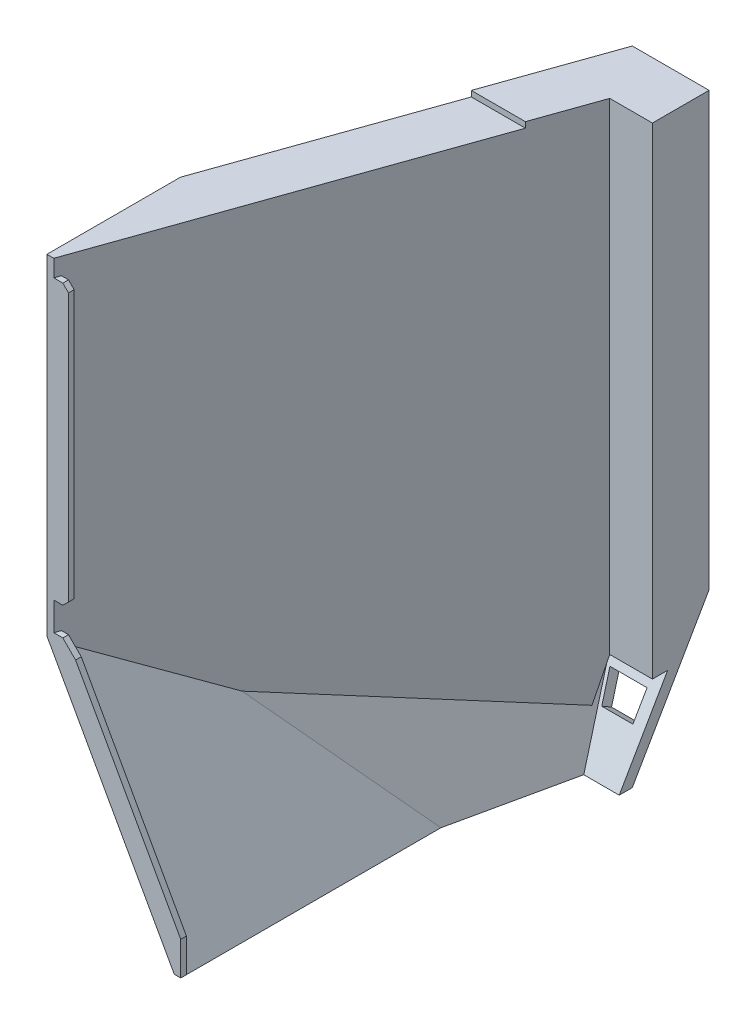
SolidWorks part; units mm, degrees
ref_plane "Plan de face" through (0, 0, 0) normal (0, 0, 1) x (1, 0, 0)
ref_plane "Plan de dessus" through (0, 0, 0) normal (0, 1, 0) x (1, 0, 0)
ref_plane "Plan de droite" through (0, 0, 0) normal (1, 0, 0) x (0, 0, -1)
sketch "Esquisse1" plane through (0, 0, 0) normal (0, 1, 0) x (1, 0, 0)
  line L0 (-258, 0) -> (-258, 609.9611) construction
  line L1 (-258, 609.9611) -> (-42.4247, 0) construction
  line L2 (-42.4247, 0) -> (-258, 0) construction
  line L3 (-42.4247, 0) -> (0, 0) construction
  line L4 (0, 0) -> (-258, 730) construction
  line L5 (-258, 609.9611) -> (-258, 730) construction
  line L6 (0, 0) -> (95.4556, 0)
  line L7 (95.4556, 0) -> (-196.1198, 825)
  line L8 (0, 0) -> (-291.5753, 825)
  line L9 (-291.5753, 825) -> (-196.1198, 825)
  line L10 (-196.1198, 825) -> (-196.1198, 0) construction
  dimension "D1" = 40
  dimension "D2" = 258
  dimension "D3" = 730
  dimension "D4" = 825
  dimension "D5" = 90
extrude "Boss.-Extru.2" add sketch "Esquisse1" along normal blind 850
sketch "Esquisse2" plane through (0, 0, -825) normal (0, 0, -1) x (-1, 0, 0)
  line L0 (196.1198, 850) -> (196.1198, 0) construction
  line L1 (196.1198, 0) -> (331.5753, 0)
  line L2 (196.1198, 0) -> (196.1198, 850)
  line L3 (196.1198, 850) -> (331.5753, 850)
  line L4 (331.5753, 0) -> (331.5753, 850)
  line L5 (196.1198, 0) -> (291.5753, 0) construction
  line L6 (196.1198, 850) -> (291.5753, 850) construction
  line L7 (291.5753, 850) -> (291.5753, 0) construction
  dimension "D1" = 40
extrude "Boss.-Extru.4" add sketch "Esquisse2" against normal blind 100
sketch "Esquisse7" plane through (-331.5753, 0, 0) normal (-1, 0, 0) x (0, 0, 1)
  line L0 (0, 850) -> (0, 0) construction
  line L1 (-615, 850) -> (0, 850)
  line L2 (-615, 850) -> (-615, 840)
  line L3 (-615, 840) -> (0, 840)
  line L4 (0, 850) -> (0, 840)
  line L5 (-725, 850) -> (0, 850) construction
  line L6 (-725, 0) -> (-725, 850) construction
  dimension "D1" = 10
  dimension "D2" = 110
extrude "Enlèv. mat.-Extru.5" cut sketch "Esquisse7" against normal through all
sketch "Esquisse8" plane through (84.8562, 0, -29.9903) normal (0.9428, 0, -0.3332) x (-0.3332, 0, -0.9428)
  line L0 (-31.8082, 280) -> (768.9475, 0)
  line L1 (-31.8082, 840) -> (-31.8082, 0) construction
  line L2 (-31.8082, 0) -> (843.201, 0) construction
  line L3 (768.9475, 0) -> (-31.8082, 0)
  line L4 (-31.8082, 0) -> (-31.8082, 280)
  dimension "D1" = 280
extrude "Enlèv. mat.-Extru.6" cut sketch "Esquisse8" against normal through all
chamfer "Chanfrein1" distance 40 angle 69 1 edges at (-37.9605, 140, -377.4951)
chamfer "Chanfrein2" distance 50 angle 60 1 edges at (-279.3754, 0, -825)
chamfer "Chanfrein3" distance 250 angle 19 1 edges at (95.4556, 615.1952, 0)
sketch "Esquisse11" plane through (0, 0, -825) normal (0, 0, -1) x (-1, 0, 0)
  line L0 (311.5753, 850) -> (311.5753, 86.6025) construction
  line L1 (196.1198, 86.6025) -> (331.5753, 86.6025) construction
  line L2 (311.5753, 86.6025) -> (216.1198, 86.6025) construction
  line L3 (216.1198, 86.6025) -> (216.1198, 850) construction
  line L4 (196.1198, 850) -> (331.5753, 850) construction
  line L5 (331.5753, 86.6025) -> (331.5753, 850) construction
  line L6 (196.1198, 850) -> (196.1198, 86.6025) construction
  line L7 (289.0753, 679.7722) -> (238.6198, 730.2278) construction
  line L8 (273.1654, 663.8623) -> (222.7099, 714.3179)
  line L9 (304.9852, 695.6821) -> (254.5297, 746.1377)
  line L10 (289.0753, 539.7722) -> (238.6198, 590.2278) construction
  line L11 (273.1654, 523.8623) -> (222.7099, 574.3179)
  line L12 (304.9852, 555.6821) -> (254.5297, 606.1377)
  line L13 (289.0753, 399.7722) -> (238.6198, 450.2278) construction
  line L14 (273.1654, 383.8623) -> (222.7099, 434.3179)
  line L15 (304.9852, 415.6821) -> (254.5297, 466.1377)
  line L16 (289.0753, 259.7722) -> (238.6198, 310.2278) construction
  line L17 (273.1654, 243.8623) -> (222.7099, 294.3179)
  line L18 (304.9852, 275.6821) -> (254.5297, 326.1377)
  line L19 (263.8476, 850) -> (263.8476, 86.6025) construction
  arc A0 (273.1654, 663.8623) -> (304.9852, 695.6821) centre (289.0753, 679.7722) ccw
  arc A1 (254.5297, 746.1377) -> (222.7099, 714.3179) centre (238.6198, 730.2278) ccw
  arc A2 (273.1654, 523.8623) -> (304.9852, 555.6821) centre (289.0753, 539.7722) ccw
  arc A3 (254.5297, 606.1377) -> (222.7099, 574.3179) centre (238.6198, 590.2278) ccw
  arc A4 (273.1654, 383.8623) -> (304.9852, 415.6821) centre (289.0753, 399.7722) ccw
  arc A5 (254.5297, 466.1377) -> (222.7099, 434.3179) centre (238.6198, 450.2278) ccw
  arc A6 (273.1654, 243.8623) -> (304.9852, 275.6821) centre (289.0753, 259.7722) ccw
  arc A7 (254.5297, 326.1377) -> (222.7099, 294.3179) centre (238.6198, 310.2278) ccw
  point P14 (263.8476, 705)
  point P23 (263.8476, 565)
  point P30 (263.8476, 425)
  point P37 (263.8476, 285)
  dimension "D1" = 20
  dimension "D2" = 20
  dimension "D3" = 45
  dimension "D4" = 45
  dimension "D5" = 145
  dimension "D7" = 140
  dimension "D6" = 4
extrude "Enlèv. mat.-Extru.9" cut sketch "Esquisse11" against normal blind 20
sketch "Esquisse12" plane through (-40.7197, 14.9785, 8.8363) normal (0.9196, -0.3383, -0.1996) x (-0.179, 0.0914, -0.9796)
  line L0 (758.2962, -87.7609) -> (129.5106, 220.361)
  line L1 (763.9526, -90.5327) -> (129.5106, 220.361) construction
  line L2 (129.5106, 220.361) -> (128.594, -274.639)
  line L3 (128.594, -274.639) -> (551.3872, -304.9904)
  line L4 (551.3872, -304.9904) -> (758.2962, -87.7609)
  line L5 (129.5106, 220.361) -> (22.2049, 258.2803) construction
  dimension "D1" = 64
  dimension "D2" = 72.5
  dimension "D3" = 495
  dimension "D4" = 94
  dimension "D5" = 300
extrude "Boss.-Extru.5" add sketch "Esquisse12" against normal blind 20
sketch "Esquisse13" plane through (0, -335.5848, -581.25) normal (0, -0.5, -0.866) x (-1, 0, 0)
  line L0 (331.5753, 387.5) -> (216.3252, 387.5)
  line L1 (331.5753, 387.5) -> (331.5753, -161.1549)
  line L2 (216.3252, 387.5) -> (195.754, 485.4301) construction
  line L3 (216.3252, 387.5) -> (331.5753, -161.1549)
extrude "Boss.-Extru.6" add sketch "Esquisse13" against normal blind 20
ref_plane "Plan1" through (-40.7197, 14.9785, 8.8363) normal (-0.9196, 0.3383, 0.1996) x (0.1873, -0.0689, 0.9799)
sketch "Esquisse14" plane through (-40.7197, 14.9785, 8.8363) normal (-0.9196, 0.3383, 0.1996) x (0.1873, -0.0689, 0.9799)
  line L0 (-558.5436, -291.6781) -> (-760.183, -69.5485)
  line L1 (-760.183, -69.5485) -> (-765.9042, -72.1839)
  line L2 (-765.9042, -72.1839) -> (-799.9273, -74.6815)
  line L3 (-799.9273, -74.6815) -> (-671.7428, -297.0794)
  line L4 (-799.9273, -74.6815) -> (-519.9684, -560.4054) construction
  line L5 (-671.7428, -297.0794) -> (-558.5436, -291.6781)
  line L6 (-135.144, -271.4758) -> (-558.5436, -291.6781) construction
extrude "Boss.-Extru.7" add sketch "Esquisse14" against normal up to surface (20 mm away)
sketch "Esquisse17" plane through (14.0599, 0, -0.114) normal (1, 0, -0.0081) x (-0.0081, 0, -1)
  line L0 (0, 268.8776) -> (0, -254.3755)
  line L1 (0, -254.3755) -> (124.8806, -230.4959)
  line L2 (124.8806, -230.4959) -> (112.7434, 233.2032)
  line L3 (112.7434, 233.2032) -> (0, 268.8776)
extrude "Boss.-Extru.8" add sketch "Esquisse17" against normal up to surface (194.5156 mm away)
sketch "Esquisse19" plane through (-27.916, 239.584, -78.9873) normal (0.11, -0.944, 0.3112) x (-0.9939, -0.1045, 0.0344)
  line L0 (-42.2331, -84.7006) -> (-41.8492, -35.1412)
  line L1 (-41.3123, 34.1614) -> (-42.2331, -84.7006) construction
  line L2 (-42.2331, -84.7006) -> (-28.0864, -84.1877)
  line L3 (-28.0864, -84.1877) -> (229.7105, 688.5453)
  line L4 (229.7105, 688.5453) -> (202.6022, 697.5891)
  line L5 (202.6022, 697.5891) -> (-41.8492, -35.1412)
  line L6 (-28.0864, -84.1877) -> (-42.2331, -84.7006) construction
  point P1 (-35.1598, -84.4442)
extrude "Boss.-Extru.14" add sketch "Esquisse19" along normal up to surface up to face at (-137.213, -20.9481, -274.708)
sketch "Esquisse20" plane through (0, 0, 0) normal (0, 1, 0) x (1, 0, 0)
  line L1 (14.0608, 0) -> (-22.7378, 0)
  line L2 (14.0608, 0) -> (14.0608, -35.8353)
  line L3 (14.0608, -35.8353) -> (-22.7378, -35.8353)
  line L4 (-22.7378, 0) -> (-22.7378, -35.8353)
extrude "Enlèv. mat.-Extru.11" cut sketch "Esquisse20" against normal through all both and the other way through all
sketch "Esquisse15" plane through (0, 0, 0) normal (0, 0, 1) x (1, 0, 0)
  line L0 (-331.5753, 86.6025) -> (-331.5753, -475.1491) construction
  line L1 (-331.5753, -190.1491) -> (14.0599, -190.1491) construction
  line L2 (-331.5753, -190.1491) -> (-331.5753, -475.1491)
  line L3 (-331.5753, -475.1491) -> (14.0599, -475.1491)
  line L4 (14.0599, -190.1491) -> (14.0599, -475.1491)
  line L6 (14.0599, 228.3016) -> (14.0599, -254.3755) construction
  line L7 (14.0599, -190.1491) -> (14.0608, 259.8509) construction
  line L8 (14.0608, 270.516) -> (14.0608, 840) construction
  line L9 (14.0608, 259.8509) -> (-235.9401, -190.1491)
  line L10 (14.0608, 259.8509) -> (14.0608, 270.516)
  line L11 (55.8469, 19.8509) -> (55.8469, -190.1491)
  line L12 (55.8469, -190.1491) -> (14.0599, -190.1491)
  line L13 (55.8469, 270.516) -> (55.8469, 19.8509)
  line L14 (-331.5753, -190.1491) -> (-235.9401, -190.1491)
  line L16 (14.0608, 270.516) -> (55.8469, 270.516)
  dimension "D1" = 285
  dimension "D2" = 450
  dimension "D3" = 250
extrude "Enlèv. mat.-Extru.10" cut sketch "Esquisse15" against normal through all both and the other way through all
sketch "Esquisse21" plane through (-99.5697, 55.3167, 0) normal (0.8742, -0.4856, 0) x (0, 0, -1)
  line L0 (321.4247, -305.5422) -> (543.0684, -280.803)
  line L1 (543.0684, -280.803) -> (155.7737, 231.3776)
  line L2 (155.7737, 231.3776) -> (0, 233.979)
  line L3 (0, 233.979) -> (0, 205.026)
  line L4 (0, 205.026) -> (0, -305.5422)
  line L5 (0, -305.5422) -> (321.4247, -305.5422)
extrude "Boss.-Extru.15" add sketch "Esquisse21" against normal blind 10
sketch "Esquisse23" plane through (0, 0, 0) normal (0, 0, 1) x (1, 0, 0)
  line L0 (-331.5753, -190.1491) -> (-331.5753, -260.8164)
  line L1 (-331.5753, -190.1491) -> (-102.0825, -190.1491) construction
  line L2 (-331.5753, -190.1491) -> (-331.5753, -148.1491)
  line L3 (-331.5753, -148.1491) -> (-102.0825, -148.1491)
  line L4 (-102.0825, -190.1491) -> (-102.0825, -148.1491)
  line L5 (-331.5753, -260.8164) -> (-102.0825, -260.8164)
  line L6 (-102.0825, -190.1491) -> (-102.0825, -260.8164)
  point P0 (-331.5753, -190.1491)
  dimension "D1" = 42
extrude "Enlèv. mat.-Extru.12" cut sketch "Esquisse23" against normal through all
sketch "Esquisse26" plane through (0, 0, 0) normal (0, 0, 1) x (1, 0, 0)
  line L0 (-224.0463, -148.1491) -> (-224.0463, 810) construction
  line L1 (-224.0463, 810) -> (14.0608, 810) construction
  line L2 (14.0608, 270.516) -> (14.0608, 840) construction
  line L3 (14.0608, 810) -> (14.0608, 317.5769)
  line L4 (14.0608, 317.5769) -> (-25.9392, 317.5769)
  line L5 (-25.9392, 317.5769) -> (-25.9392, 267.5769) construction
  line L6 (-25.9392, 267.5769) -> (14.0608, 267.5769)
  line L7 (14.0608, 267.5769) -> (12.7975, 257.5769)
  line L8 (12.7975, 257.5769) -> (-212.6067, -148.1491)
  line L9 (-212.6067, -148.1491) -> (-224.0463, -148.1491)
  line L10 (0, 840) -> (-217.3562, 840) construction
  line L13 (-25.9392, 267.5769) -> (-224.0463, -89.0145)
  line L14 (-224.0463, -89.0145) -> (-224.0463, -148.1491)
  line L15 (-25.9392, 810) -> (14.0608, 810) construction
  line L16 (0, 255.1327) -> (-224.0463, -148.1491) construction
  line L17 (14.0608, 810) -> (14.0608, 840)
  line L18 (14.0608, 840) -> (0, 840)
  line L19 (0, 840) -> (0, 810)
  line L20 (0, 810) -> (-25.9392, 810)
  line L22 (-25.9392, 810) -> (-25.9392, 317.5769)
  dimension "D1" = 30
  dimension "D2" = 50
  dimension "D3" = 10
  dimension "D4" = 40
extrude "Boss.-Extru.17" add sketch "Esquisse26" against normal blind 10
sketch "Esquisse24" plane through (14.0599, 0, -0.114) normal (1, 0, -0.0081) x (-0.0081, 0, -1)
  line L0 (-0.114, 259.8509) -> (155.6647, 257.5769)
  line L1 (155.6647, 257.5769) -> (33.6338, 259.3583) construction
  line L2 (-0.114, 259.8509) -> (-0.114, 840)
  line L3 (-0.114, 840) -> (235.6055, 840)
  line L5 (235.6055, 840) -> (235.6055, 302.9729)
  line L6 (235.6055, 302.9729) -> (155.6647, 257.5769)
extrude "Enlèv. mat.-Extru.13" cut sketch "Esquisse24" along normal blind 10
chamfer "Chanfrein6" distance 10 angle 45 3 edges at (-25.9392, 810, -5) (-25.9392, 267.5769, -5) (-25.9392, 317.5769, -5)
sketch "Esquisse9" plane through (0, -335.5848, -581.25) normal (0, -0.5, -0.866) x (-1, 0, 0)
  line L4 (311.5753, 438.3869) -> (226.0724, 438.3869)
  line L5 (226.0724, 438.3869) -> (236.5753, 388.3869)
  line L6 (236.5753, 388.3869) -> (311.5753, 388.3869)
  line L7 (311.5753, 388.3869) -> (311.5753, 438.3869)
  line L8 (219.9569, 467.5) -> (268.4949, 236.4322)
  line L9 (268.4949, 236.4322) -> (311.5753, 236.4322)
  line L10 (311.5753, 236.4322) -> (311.5753, 467.5)
  line L11 (311.5753, 467.5) -> (219.9569, 467.5)
  line L12 (219.9569, 467.5) -> (268.4949, 236.4322) construction
  line L13 (268.4949, 236.4322) -> (311.5753, 236.4322) construction
  line L14 (311.5753, 236.4322) -> (311.5753, 467.5) construction
  line L15 (311.5753, 467.5) -> (219.9569, 467.5) construction
  line L16 (236.5753, 388.3869) -> (236.5753, 438.3869) construction
  line L17 (311.5753, 343.1758) -> (246.0724, 343.1758)
  line L18 (246.0724, 343.1758) -> (256.5753, 293.1758)
  line L19 (256.5753, 293.1758) -> (311.5753, 293.1758)
  line L20 (311.5753, 293.1758) -> (311.5753, 343.1758)
  dimension "D2" = 50
  dimension "D3" = 75
  dimension "D4" = 50
  dimension "D5" = 55
  dimension "D1" = 20
extrude "Enlèv. mat.-Extru.7" cut sketch "Esquisse9" against normal blind 20
sketch "Esquisse28" plane through (0, 0, 0) normal (0, 1, 0) x (1, 0, 0)
  line L1 (12.1492, 235.7118) -> (62.2561, 235.7118)
  line L2 (12.1492, 235.7118) -> (12.1492, 0)
  line L3 (12.1492, 0) -> (62.2561, 0)
  line L4 (62.2561, 235.7118) -> (62.2561, 0)
extrude "Enlèv. mat.-Extru.15" cut sketch "Esquisse28" along normal through all
mirror "Symétrie1" about plane through (-331.5753, 0, -725) normal (-1, 0, 0) of bodies 128
sketch "Esquisse29" plane through (0, 850, 0) normal (0, 1, 0) x (1, 0, 0)
  line L0 (-196.1198, 825) -> (-467.0309, 825) construction
  line L1 (-331.5753, 825) -> (306.2718, 825)
  line L2 (-331.5753, 825) -> (-331.5753, -468.2685)
  line L3 (-331.5753, -468.2685) -> (306.2718, -468.2685)
  line L4 (306.2718, 825) -> (306.2718, -468.2685)
extrude "Enlèv. mat.-Extru.16" cut sketch "Esquisse29" against normal through all
